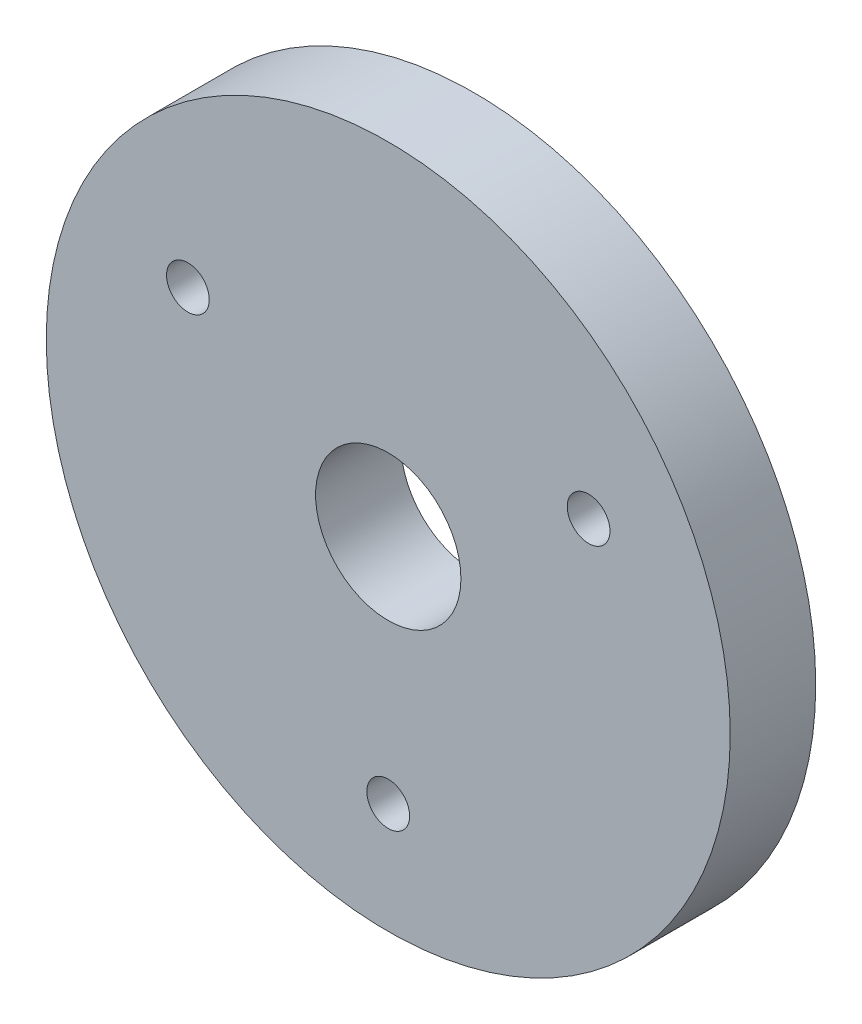
SolidWorks part; units mm, degrees
ref_plane "前视基准面" through (0, 0, 0) normal (0, 0, 1) x (1, 0, 0)
ref_plane "上视基准面" through (0, 0, 0) normal (0, 1, 0) x (1, 0, 0)
ref_plane "右视基准面" through (0, 0, 0) normal (1, 0, 0) x (0, 0, -1)
sketch "草图1" plane through (0, 0, 0) normal (0, 0, 1) x (1, 0, 0)
  circle A0 centre (0, 0) radius 4.25
  circle A6 centre (0, 0) radius 20
  circle A14 centre (0, 0) radius 13.53 construction
  circle A20 centre (0, -13.53) radius 1.25
  circle A21 centre (-11.7173, 6.765) radius 1.25
  circle A22 centre (11.7173, 6.765) radius 1.25
  dimension "D1" = 3
extrude "凸台-拉伸1" add sketch "草图1" along normal blind 5
sketch "草图4" plane through (0, 0, 0) normal (0, 0, -1) x (-1, 0, 0)
  circle A0 centre (0, 0) radius 5
sketch "草图5" plane through (0, 0, 5) normal (0, 0, 1) x (1, 0, 0)
  circle A0 centre (0, 0) radius 5
